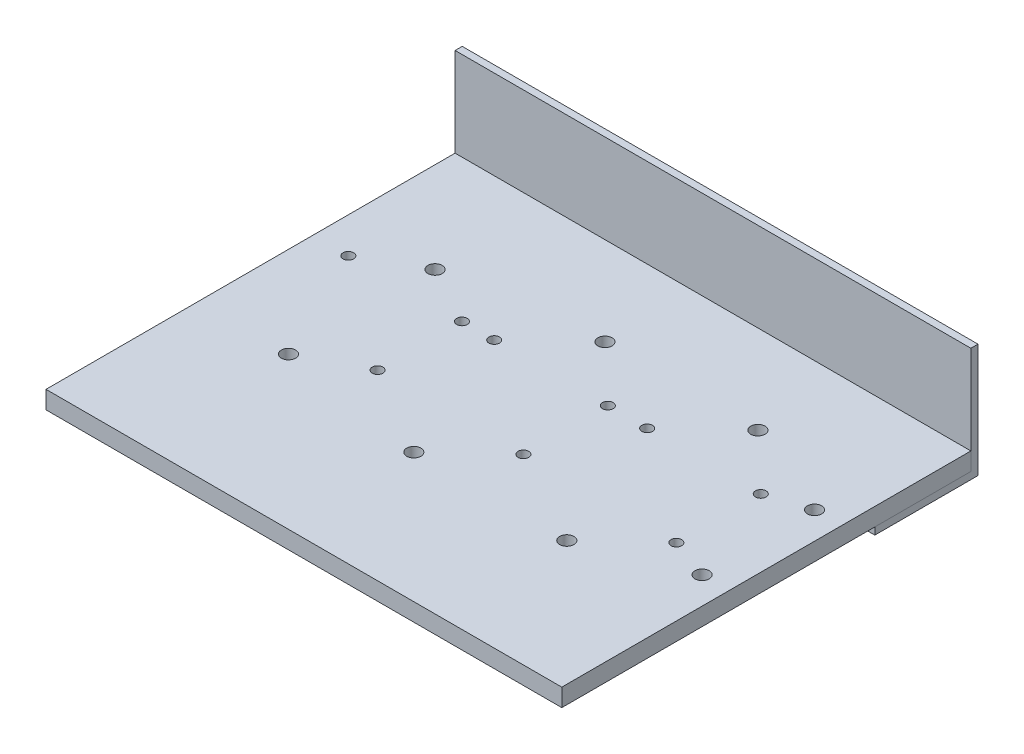
SolidWorks part; units mm, degrees
ref_plane "Front Plane" through (0, 0, 0) normal (0, 0, 1) x (1, 0, 0)
ref_plane "Top Plane" through (0, 0, 0) normal (0, 1, 0) x (1, 0, 0)
ref_plane "Right Plane" through (0, 0, 0) normal (1, 0, 0) x (0, 0, -1)
sketch "Sketch1" plane through (0, 0, 0) normal (0, 1, 0) x (1, 0, 0)
  line L1 (-72.5, 57.5) -> (72.5, 57.5)
  line L2 (-72.5, 57.5) -> (-72.5, -57.5)
  line L3 (-72.5, -57.5) -> (72.5, -57.5)
  line L4 (72.5, 57.5) -> (72.5, -57.5)
  line L5 (-72.5, 57.5) -> (72.5, -57.5) construction
  line L6 (-72.5, -57.5) -> (72.5, 57.5) construction
  point P0 (0, 0)
extrude "Boss-Extrude1" add sketch "Sketch1" along normal blind 5
sketch "Sketch2" plane through (-72.5, 0, 0) normal (-1, 0, 0) x (0, 0, 1)
  line L0 (-57.5, 0) -> (-57.5, 30)
  line L1 (-57.5, 0) -> (-30.5, 0)
  line L2 (-57.5, 0) -> (57.5, 0) construction
extrude "Extrude-Thin1" add sketch "Sketch2" against normal blind 145 separate body thin thin type one direction wall 2
sketch "Sketch3" plane through (0, 5, 0) normal (0, 1, 0) x (1, 0, 0)
  line L0 (-62.5, 17.5) -> (82.7601, 17.5) construction
  line L1 (-72.5, 57.5) -> (-72.5, -57.5) construction
  line L2 (74, 5.3707) -> (94.3871, 5.3707) construction
  circle A0 centre (-62.5, 17.5) radius 1.5
  circle A1 centre (-30.5682, 17.5) radius 1.5
  circle A2 centre (-30.5682, -6.2266) radius 1.5
  circle A3 centre (-21.5, 17.5) radius 1.5
  circle A4 centre (10.4318, 17.5) radius 1.5
  circle A5 centre (10.4318, -6.2266) radius 1.5
  circle A6 centre (21.5, 17.5) radius 1.5
  circle A7 centre (53.4318, 17.5) radius 1.5
  circle A8 centre (53.4318, -6.2266) radius 1.5
  circle A9 centre (64.8701, 21.1793) radius 2
  circle A10 centre (64.8701, -10.4379) radius 2
  circle A11 centre (-46.9937, -14.8427) radius 2
  circle A12 centre (-46.9937, 26.3587) radius 2
  circle A13 centre (-5.4937, 32.6189) radius 2
  circle A14 centre (37.5063, 32.6189) radius 2
  circle A15 centre (-5.4937, -21.103) radius 2
  circle A16 centre (37.5063, -21.103) radius 2
  dimension "D1" = 51
  dimension "D2" = 94
extrude "Cut-Extrude1" cut sketch "Sketch3" against normal through all
sketch "Sketch4" plane through (0, -2, 0) normal (0, -1, 0) x (1, 0, 0)
  circle A0 centre (-5.4937, -32.6189) radius 8
  circle A1 centre (37.5063, -32.6189) radius 8
extrude "Cut-Extrude2" cut sketch "Sketch4" against normal up to surface (2 mm away) up to face at (37.5063, 0, 23.103)
